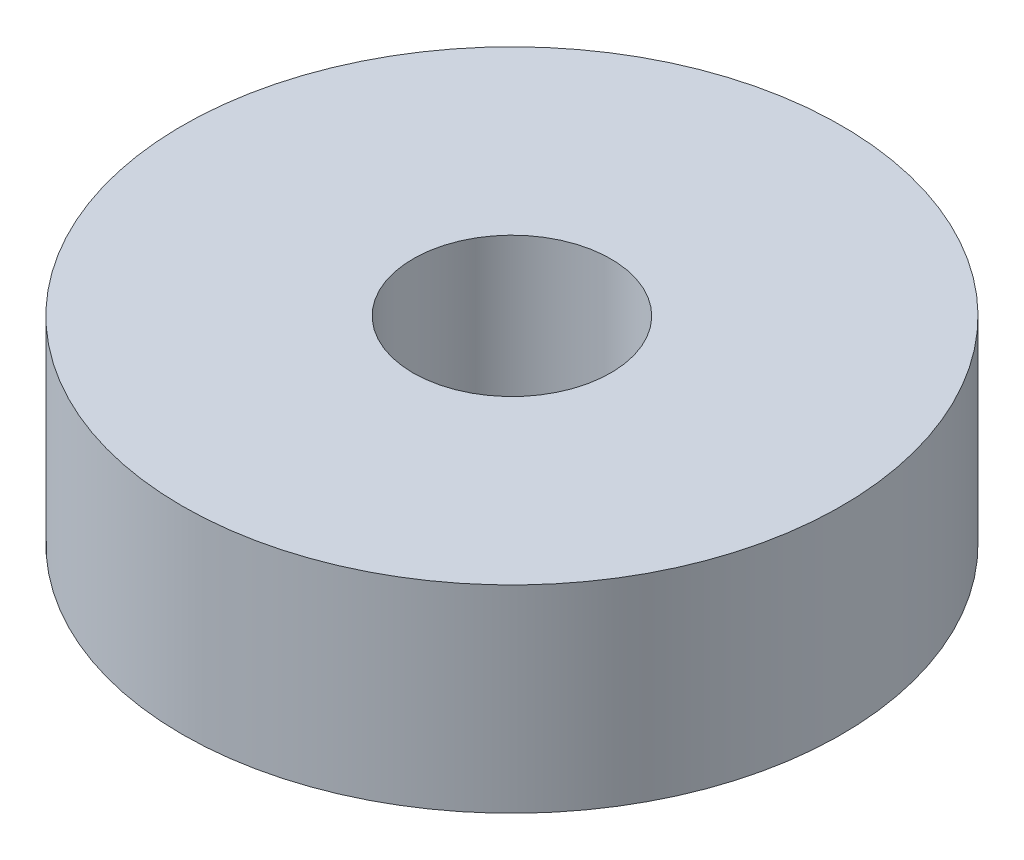
SolidWorks part; units mm, degrees
ref_plane "Front" through (0, 0, 0) normal (0, 0, 1) x (1, 0, 0)
ref_plane "Top" through (0, 0, 0) normal (0, 1, 0) x (1, 0, 0)
ref_plane "Right" through (0, 0, 0) normal (1, 0, 0) x (0, 0, -1)
sketch "Sketch1" plane through (0, 0, 0) normal (0, 1, 0) x (1, 0, 0)
  circle A0 centre (0, 0) radius 5
  circle A1 centre (0, 0) radius 1.5
  dimension "D1" = 10
  dimension "D2" = 3
extrude "Boss-Extrude1" add sketch "Sketch1" along normal blind 3
